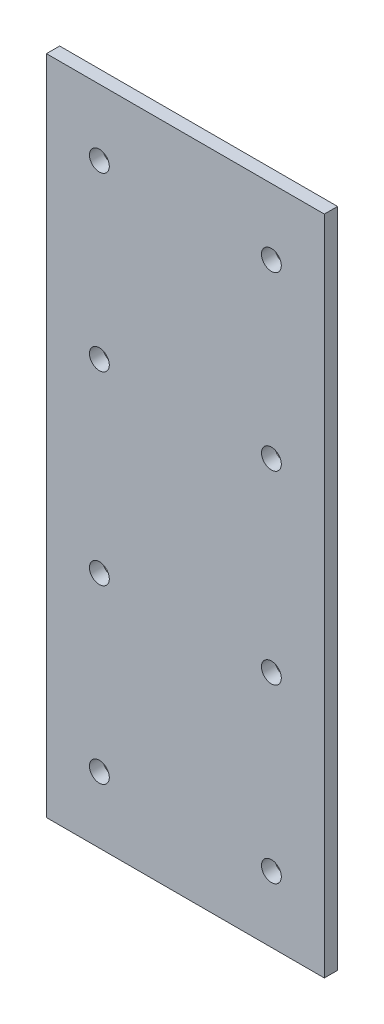
SolidWorks part; units mm, degrees
ref_plane "Front Plane" through (0, 0, 0) normal (0, 0, 1) x (1, 0, 0)
ref_plane "Top Plane" through (0, 0, 0) normal (0, 1, 0) x (1, 0, 0)
ref_plane "Right Plane" through (0, 0, 0) normal (1, 0, 0) x (0, 0, -1)
sketch "Sketch1" plane through (0, 0, 0) normal (0, 0, 1) x (1, 0, 0)
  line L1 (21, -50) -> (-21, -50)
  line L2 (21, -50) -> (21, 50)
  line L3 (21, 50) -> (-21, 50)
  line L4 (-21, -50) -> (-21, 50)
  line L5 (21, -50) -> (-21, 50) construction
  line L6 (21, 50) -> (-21, -50) construction
  point P0 (0, 0)
  dimension "D1" = 42
  dimension "D2" = 100
extrude "Boss-Extrude1" add sketch "Sketch1" along normal blind 2
sketch "Sketch2" plane through (0, 0, 2) normal (0, 0, 1) x (1, 0, 0)
  line L0 (-21, -50) -> (21, -50) construction
  line L1 (0, 0) -> (0, -50) construction
  line L2 (-21, 50) -> (-21, -50) construction
  line L5 (0, 0) -> (-21, 0) construction
  circle A0 centre (-13, -40) radius 1.5
  circle A1 centre (13, -40) radius 1.5
  circle A2 centre (13, -14) radius 1.5
  circle A3 centre (-13, -14) radius 1.5
  circle A4 centre (13, 40) radius 1.5
  circle A5 centre (-13, 40) radius 1.5
  circle A6 centre (13, 14) radius 1.5
  circle A7 centre (-13, 14) radius 1.5
  dimension "D1" = 3
  dimension "D2" = 10
  dimension "D3" = 3
  dimension "D6" = 10
  dimension "D7" = 26
  dimension "D10" = 8
  dimension "D11" = 3
  dimension "D12" = 3
  dimension "D4" = 26
  dimension "D5" = 13
  dimension "D8" = 26
  dimension "D9" = 26
extrude "Cut-Extrude1" cut sketch "Sketch2" against normal blind 2
